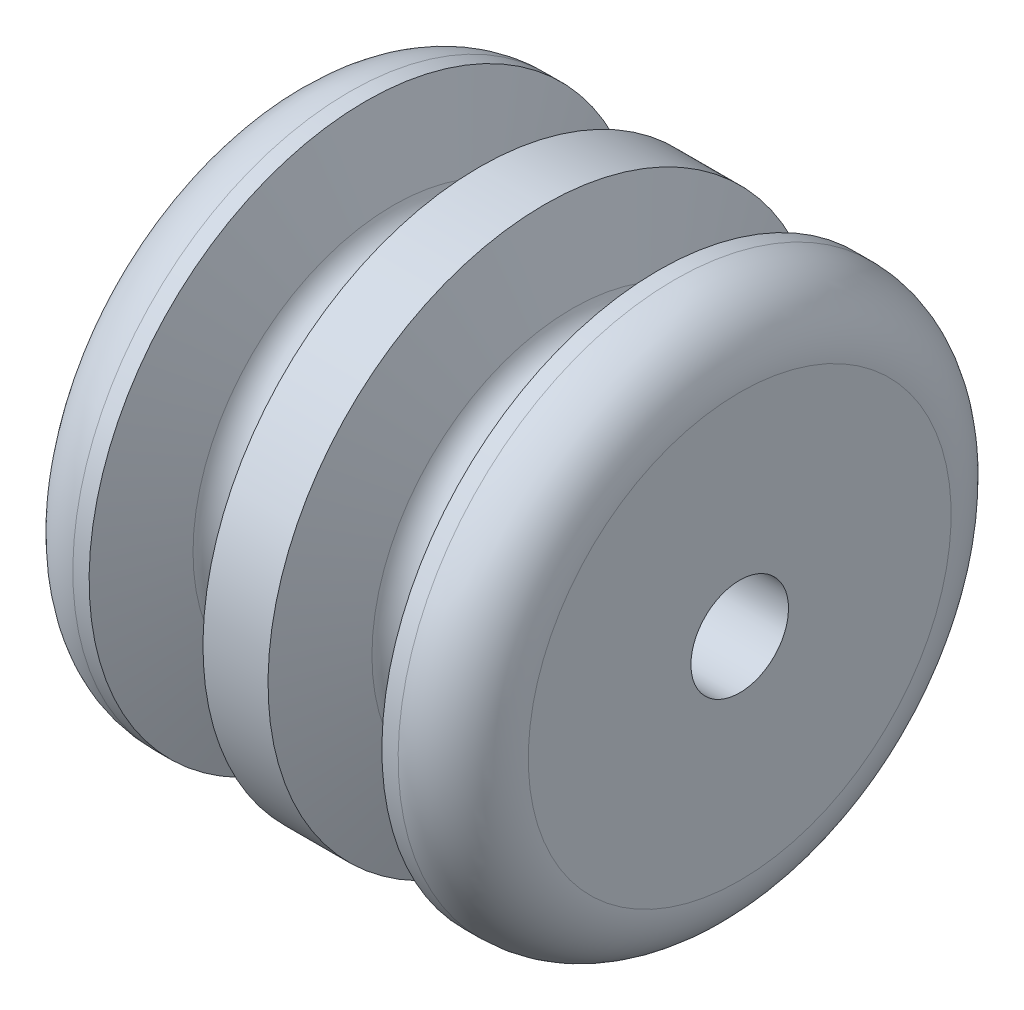
SolidWorks part; units mm, degrees
ref_plane "Front Plane" through (0, 0, 0) normal (0, 0, 1) x (1, 0, 0)
ref_plane "Top Plane" through (0, 0, 0) normal (0, 1, 0) x (1, 0, 0)
ref_plane "Right Plane" through (0, 0, 0) normal (1, 0, 0) x (0, 0, -1)
sketch "Sketch1" plane through (0, 0, 0) normal (0, 0, 1) x (1, 0, 0)
  line L0 (0, 70.2725) -> (0, -36.085) construction
  line L1 (35.56, 0) -> (-35.56, 0)
  line L2 (-35.56, 0) -> (-35.56, 33.02)
  line L3 (-25.4, 43.18) -> (-22.86, 43.18)
  line L4 (-22.86, 43.18) -> (-18.5297, 31.2825)
  line L6 (-9.4103, 31.2825) -> (-5.08, 43.18)
  line L7 (-5.08, 43.18) -> (5.08, 43.18)
  line L8 (9.4103, 31.2825) -> (5.08, 43.18)
  line L10 (22.86, 43.18) -> (18.5297, 31.2825)
  line L11 (25.4, 43.18) -> (22.86, 43.18)
  line L12 (35.56, 0) -> (35.56, 33.02)
  arc A4 (25.4, 43.18) -> (35.56, 33.02) centre (25.4, 33.02) cw
  arc A5 (-35.56, 33.02) -> (-25.4, 43.18) centre (-25.4, 33.02) cw
  arc A6 (-18.5297, 31.2825) -> (-9.4103, 31.2825) centre (-13.97, 32.9421) ccw
  arc A7 (18.5297, 31.2825) -> (9.4103, 31.2825) centre (13.97, 32.9421) cw
  point P13 (0, 43.18)
  point P18 (0, 0)
  point P23 (10.6269, 27.94)
  point P32 (35.56, 43.18)
  point P35 (-35.56, 43.18)
  dimension "D10" = 10.16
  dimension "D1" = 43.18
  dimension "D2" = 35.56
  dimension "D3" = 12.7
  dimension "D4" = 5.08
  dimension "D8" = 43.18
revolve "Revolve1" add sketch "Sketch1" angle 360 about L1
sketch "Sketch5" plane through (35.56, 0, 0) normal (1, 0, 0) x (0, 0, -1)
  circle A0 centre (0, 0) radius 7.62
  dimension "D1" = 15.24
extrude "Cut-Extrude2" cut sketch "Sketch5" against normal through all
